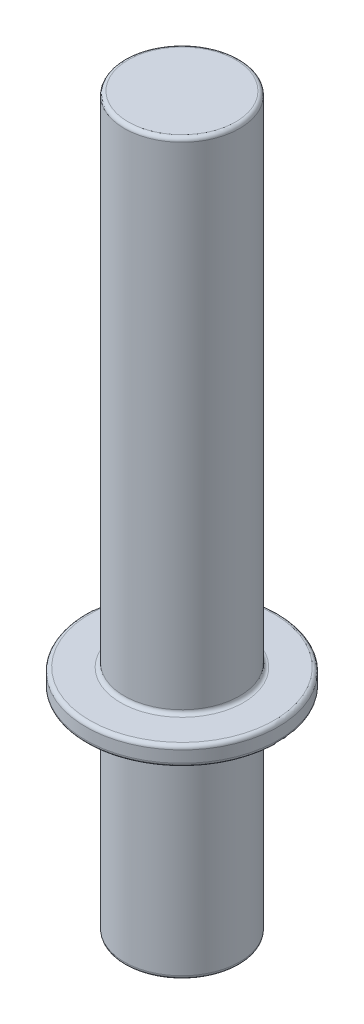
SolidWorks part; units mm, degrees
ref_plane "前视基准面" through (0, 0, 0) normal (0, 0, 1) x (1, 0, 0)
ref_plane "上视基准面" through (0, 0, 0) normal (0, 1, 0) x (1, 0, 0)
ref_plane "右视基准面" through (0, 0, 0) normal (1, 0, 0) x (0, 0, -1)
sketch "草图1" plane through (0, 0, 0) normal (0, 1, 0) x (1, 0, 0)
  circle A0 centre (0, 0) radius 1.5
extrude "凸台-拉伸1" add sketch "草图1" along normal blind 19
ref_plane "基准面1" through (0, 6, 0) normal (0, 1, 0) x (1, 0, 0)
sketch "草图3" plane through (0, 0, 0) normal (0, -1, 0) x (-1, 0, 0)
  circle A0 centre (0, 0) radius 1.5
  circle A1 centre (0, 0) radius 2.5
extrude "凸台-拉伸3" add sketch "草图3" along normal blind 0.5 from offset 6 offset against normal yes
fillet "圆角1" radius 0.1 5 edges at (0, 19, 1.5) (0, 0, 1.5) (0, 5.5, -2.5) (0, 6, -1.5) (0, 6, -2.5)
